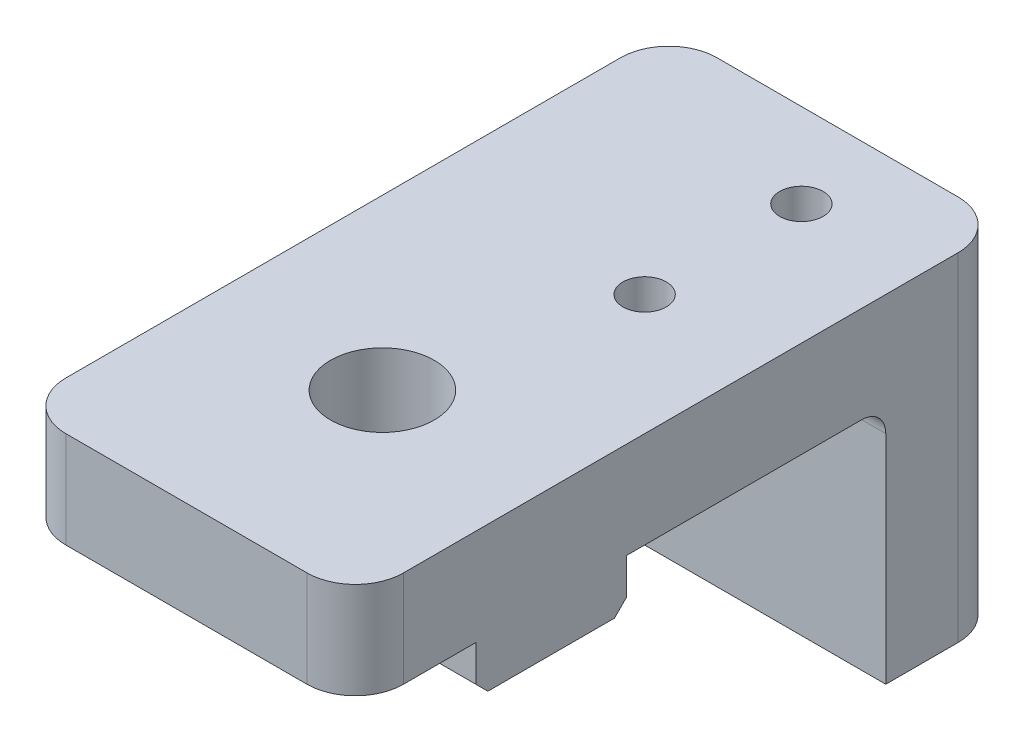
SolidWorks part; units mm, degrees
ref_plane "Front Plane" through (0, 0, 0) normal (0, 0, 1) x (1, 0, 0)
ref_plane "Top Plane" through (0, 0, 0) normal (0, 1, 0) x (1, 0, 0)
ref_plane "Right Plane" through (0, 0, 0) normal (1, 0, 0) x (0, 0, -1)
sketch "Sketch2" plane through (0, 0, 0) normal (0, 1, 0) x (1, 0, 0)
  line L1 (14, 0) -> (0, 0)
  line L2 (14, 0) -> (14, 22)
  line L3 (14, 22) -> (0, 22)
  line L4 (0, 0) -> (0, 22)
  line L6 (14, 0) -> (0, 0)
  line L7 (14, 0) -> (14, -5)
  line L8 (14, -5) -> (0, -5)
  line L9 (0, 0) -> (0, -5)
  dimension "D1" = 22
  dimension "D2" = 14
  dimension "D3" = 5
extrude "Boss-Extrude1" add sketch "Sketch2" along normal blind 4 contours L4 L1 L2 L3 | L1 L9 L8 L7
sketch "Sketch4" plane through (0, 0, 0) normal (0, -1, 0) x (-1, 0, 0)
  line L1 (0, 6.25) -> (-14, 6.25)
  line L2 (0, 6.25) -> (0, 0)
  line L3 (0, 0) -> (-14, 0)
  line L4 (-14, 6.25) -> (-14, 0)
  line L6 (0, -5) -> (0, 22) construction
  line L7 (-14, -5) -> (-14, 22) construction
  line L8 (-14, -5) -> (0, -5) construction
  dimension "D1" = 6.25
  dimension "D2" = 11.25
extrude "Boss-Extrude2" add sketch "Sketch4" along normal blind 2
sketch "Sketch3" plane through (0, 4, 0) normal (0, 1, 0) x (1, 0, 0)
  line L7 (0, 3.125) -> (14, 3.125) construction
  line L8 (14, 6.25) -> (14, 0) construction
  line L9 (14, -5) -> (14, 22) construction
  line L10 (14, 22) -> (0, 22) construction
  line L11 (0, -5) -> (0, 22) construction
  circle A7 centre (9, 18.5) radius 0.9
  circle A8 centre (9, 12) radius 0.9
  circle A9 centre (7, 3.125) radius 2.15
  point P15 (14, 3.125)
  point P28 (7, 3.125)
  dimension "D1" = 6.5
  dimension "D2" = 4.3
  dimension "D6" = 1.8
  dimension "D3" = 5
  dimension "D4" = 3.5
extrude "Cut-Extrude1" cut sketch "Sketch3" against normal through all
chamfer "Chamfer1" distance 0.5 angle 45 2 edges at (7, -2, -6.25) (7, -2, 0)
fillet "Fillet1" radius 2 4 edges at (14, 2, -22) (0, 2, -22) (0, 2, 5) (14, 2, 5)
sketch "Sketch5" plane through (0, -2, 0) normal (0, -1, 0) x (1, 0, 0)
  line L0 (0, -6.25) -> (14, -6.25) construction
  line L1 (11.5, -6.25) -> (2.5, -6.25)
  line L2 (11.5, -6.25) -> (11.5, 0)
  line L3 (11.5, 0) -> (2.5, 0)
  line L4 (2.5, -6.25) -> (2.5, 0)
  line L5 (14, 0) -> (0, 0) construction
  line L6 (14, -5.75) -> (14, -0.5) construction
  line L7 (0, -0.5) -> (0, -5.75) construction
  dimension "D1" = 2.5
  dimension "D2" = 2.5
extrude "Cut-Extrude2" cut sketch "Sketch5" against normal up to surface (2 mm away) up to face at (8.1, 0, -18.5)
sketch "Sketch6" plane through (0, 0, 0) normal (0, -1, 0) x (1, 0, 0)
  line L0 (0, -6.25) -> (0, -20) construction
  line L1 (14, -6.25) -> (14, -20) construction
  line L2 (12, -22) -> (2, -22) construction
  line L3 (0, -17) -> (0, -20)
  line L4 (14, -17) -> (14, -20)
  line L5 (12, -22) -> (2, -22)
  line L6 (0, -17) -> (14, -17)
  arc A0 (12, -22) -> (14, -20) centre (12, -20) ccw construction
  arc A1 (0, -20) -> (2, -22) centre (2, -20) ccw construction
  arc A2 (12, -22) -> (14, -20) centre (12, -20) ccw
  arc A3 (0, -20) -> (2, -22) centre (2, -20) ccw
  dimension "D1" = 5
extrude "Boss-Extrude3" add sketch "Sketch6" along normal blind 10
sketch "Sketch7" plane through (0, 0, -22) normal (0, 0, -1) x (-1, 0, 0)
  line L0 (-14, -3) -> (0, -3) construction
  line L1 (-14, -10) -> (-14, 4) construction
  line L2 (0, 4) -> (0, -10) construction
  line L3 (-8.75, 0.75) -> (-5.25, 0.75)
  line L4 (-8.75, 0.75) -> (-8.75, -0.75)
  line L5 (-8.75, -0.75) -> (-5.25, -0.75)
  line L6 (-5.25, 0.75) -> (-5.25, -0.75)
  line L7 (-8.75, 0.75) -> (-5.25, -0.75) construction
  line L8 (-8.75, -0.75) -> (-5.25, 0.75) construction
  point P4 (-14, -3)
  point P5 (-7, 0)
  point P10 (-7, -3)
  point P11 (0, 0)
  point P12 (0, 0)
  point P15 (0, 0)
  dimension "D1" = 3.5
  dimension "D2" = 1.5
  dimension "D3" = 3
revolve "Cut-Revolve1" cut sketch "Sketch7" angle 360 about L0
fillet "Fillet2" radius 1 1 edges at (7, 0, -17)
